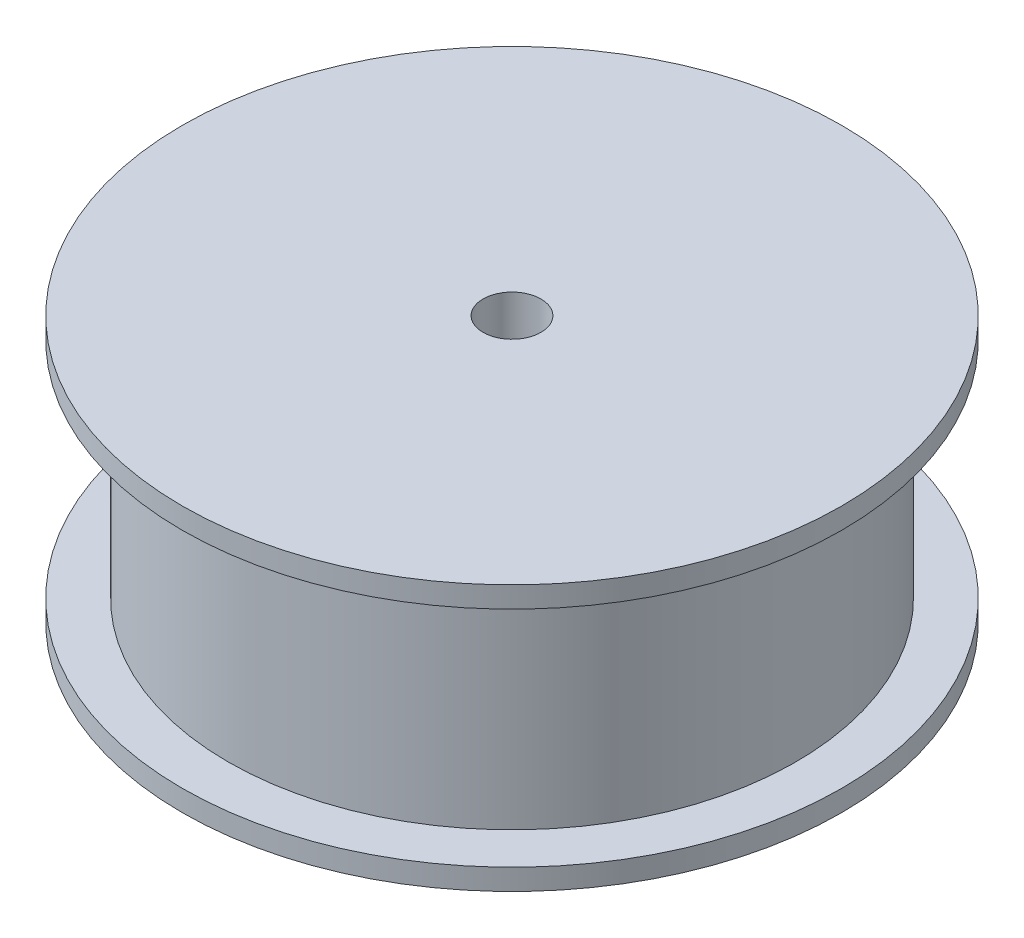
SolidWorks part; units mm, degrees
ref_plane "Front Plane" through (0, 0, 0) normal (0, 0, 1) x (1, 0, 0)
ref_plane "Top Plane" through (0, 0, 0) normal (0, 1, 0) x (1, 0, 0)
ref_plane "Right Plane" through (0, 0, 0) normal (1, 0, 0) x (0, 0, -1)
sketch "Sketch1" plane through (0, 0, 0) normal (0, 1, 0) x (1, 0, 0)
  circle A0 centre (0, 0) radius 18
  dimension "D1" = 36
extrude "Boss-Extrude1" add sketch "Sketch1" along normal blind 1.15
sketch "Sketch2" plane through (0, 1.15, 0) normal (0, 1, 0) x (1, 0, 0)
  circle A0 centre (0, 0) radius 15.5
  dimension "D1" = 31
extrude "Boss-Extrude2" add sketch "Sketch2" along normal blind 12.2
sketch "Sketch3" plane through (0, 13.35, 0) normal (0, 1, 0) x (1, 0, 0)
  circle A0 centre (0, 0) radius 18
  dimension "D1" = 36
extrude "Boss-Extrude3" add sketch "Sketch3" along normal blind 1.15
sketch "Sketch4" plane through (0, 14.5, 0) normal (0, 1, 0) x (1, 0, 0)
  circle A0 centre (0, 0) radius 1.58
  dimension "D1" = 3.16
extrude "Cut-Extrude1" cut sketch "Sketch4" against normal up to surface (14.5 mm away) up to face at (0, 0, 18)
